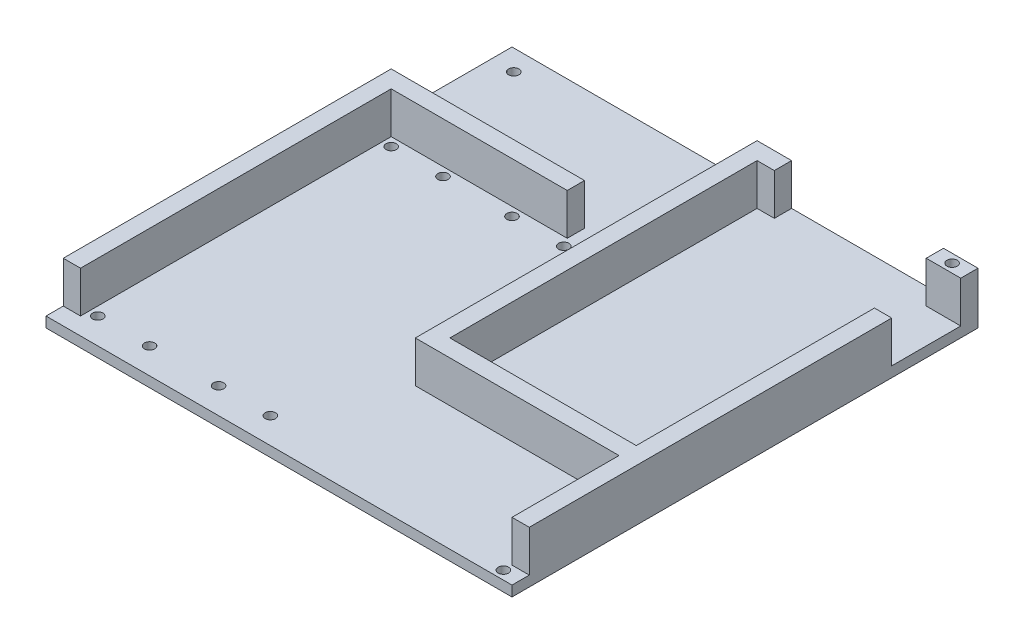
SolidWorks part; units mm, degrees
ref_plane "Front Plane" through (0, 0, 0) normal (0, 0, 1) x (1, 0, 0)
ref_plane "Top Plane" through (0, 0, 0) normal (0, 1, 0) x (1, 0, 0)
ref_plane "Right Plane" through (0, 0, 0) normal (1, 0, 0) x (0, 0, -1)
sketch "Sketch1" plane through (0, 0, 0) normal (0, 1, 0) x (1, 0, 0)
  line L1 (-65, -65) -> (65, -65)
  line L2 (-65, -65) -> (-65, 65)
  line L3 (-65, 65) -> (65, 65)
  line L4 (65, -65) -> (65, 65)
  line L5 (-65, -65) -> (65, 65) construction
  line L6 (-65, 65) -> (65, -65) construction
  line L7 (-65, -65) -> (-70, -65)
  line L8 (-65, -65) -> (-65, 65)
  line L9 (-65, 65) -> (-70, 65)
  line L10 (-70, -65) -> (-70, 65)
  point P0 (0, 0)
  dimension "D1" = 130
  dimension "D2" = 130
  dimension "D3" = 5
extrude "Boss-Extrude1" add sketch "Sketch1" along normal blind 3 contours L1 L4 L3 L2 | L10 L7 L2 L9
sketch "Sketch7" plane through (0, 3, 0) normal (0, 1, 0) x (1, 0, 0)
  line L0 (-70, -65) -> (65, -65) construction
  line L1 (-65, -65) -> (-45, -65)
  line L2 (-65, -65) -> (-65, 25)
  line L3 (-65, 25) -> (-45, 25)
  line L4 (-45, -65) -> (-45, 25)
  line L5 (-65, 22.5) -> (-45, 22.5) construction
  line L6 (-55, 25) -> (-55, -65) construction
  line L7 (-70, -65) -> (-70, 65) construction
  line L8 (-65, -20) -> (-45, -20) construction
  line L9 (-37.5, -65) -> (-37.5, 65) construction
  line L10 (-70, 65) -> (65, 65) construction
  line L11 (-10, 25) -> (-30, 25)
  line L12 (-30, -65) -> (-30, 25)
  line L13 (-10, -65) -> (-30, -65)
  line L14 (-10, -65) -> (-10, 25)
  circle A0 centre (-62.5, 22.5) radius 1.5
  circle A1 centre (-47.5, 22.5) radius 1.5
  circle A2 centre (-47.5, -62.5) radius 1.5
  circle A3 centre (-62.5, -62.5) radius 1.5
  circle A4 centre (-27.5, 22.5) radius 1.5
  circle A5 centre (-12.5, 22.5) radius 1.5
  circle A6 centre (-12.5, -62.5) radius 1.5
  circle A7 centre (-27.5, -62.5) radius 1.5
  dimension "D4" = 3
  dimension "D1" = 90
  dimension "D2" = 20
  dimension "D3" = 5
  dimension "D5" = 2.5
  dimension "D6" = 2.5
  dimension "D7" = 15
extrude "Cut-Extrude3" cut sketch "Sketch7" against normal blind 3 contours A2 | A3 | A0 | A1 | A4 | A5 | A7 | A6
sketch "Sketch8" plane through (0, 3, 0) normal (0, 1, 0) x (1, 0, 0)
  line L0 (-70, -65) -> (65, -65) construction
  line L1 (65, -65) -> (65, 65) construction
  line L2 (-70, -65) -> (65, -65)
  line L3 (65, -65) -> (65, 65)
  line L4 (-70, 65) -> (65, 65) construction
  line L5 (65, 65) -> (60, 65)
  line L6 (65, 65) -> (65, -65)
  line L7 (65, -65) -> (60, -65)
  line L8 (60, 65) -> (60, -65)
  line L9 (6, 65) -> (1, 65)
  line L10 (6, 65) -> (6, -29)
  line L11 (6, -29) -> (1, -29)
  line L12 (1, 65) -> (1, -29)
  line L14 (6, 60) -> (11, 60)
  line L15 (6, 60) -> (6, 65)
  line L16 (6, 65) -> (11, 65)
  line L17 (11, 60) -> (11, 65)
  line L18 (60, 60) -> (55, 60)
  line L19 (60, 60) -> (60, 65)
  line L20 (60, 65) -> (55, 65)
  line L21 (55, 60) -> (55, 65)
  line L22 (1, -29) -> (60, -29)
  line L23 (1, -29) -> (1, -65)
  line L24 (1, -65) -> (60, -65)
  line L25 (60, -29) -> (60, -65)
  line L26 (6, -34) -> (55, -34)
  line L27 (6, -34) -> (6, -60)
  line L28 (6, -60) -> (55, -60)
  line L29 (55, -34) -> (55, -60)
  line L30 (60, 60) -> (65, 60)
  line L31 (60, 60) -> (60, 40)
  line L32 (60, 40) -> (65, 40)
  line L33 (65, 60) -> (65, 40)
  line L34 (55, -60) -> (60, -60)
  line L35 (55, -60) -> (55, -34)
  line L36 (55, -34) -> (60, -34)
  line L37 (60, -60) -> (60, -34)
  line L38 (6, -34) -> (1, -34)
  line L39 (6, -34) -> (6, -60)
  line L40 (6, -60) -> (1, -60)
  line L41 (1, -34) -> (1, -60)
  line M22 (65, -65) -> (65, 65)
  line M23 (65, 65) -> (-70, 65)
  dimension "D1" = 5
  dimension "D2" = 5
  dimension "D3" = 54
  dimension "D4" = 5
  dimension "D5" = 5
  dimension "D6" = 5
  dimension "D7" = 5
  dimension "D8" = 94
  dimension "D9" = 5
  dimension "D10" = 20
  dimension "D11" = 5
extrude "Boss-Extrude5" add sketch "Sketch8" along normal blind 12 contours L14 L17 L10 M23 | L12 L11 L10 M23 | L21 L18 L8 M23 | L8 L30 L6 M23 | L32 L8 L2 M22 | L11 L23 L2 L8 L22 L26 L29 L28 L27
sketch "Sketch9" plane through (0, 3, 0) normal (0, 1, 0) x (1, 0, 0)
  line L0 (-70, 65) -> (1, 65) construction
  line L1 (-70, -65) -> (-70, 65) construction
  line L2 (-70, 65) -> (1, 65)
  line L3 (-70, -65) -> (-70, 65)
  line L4 (-63.5, 65) -> (-63.5, 36.7574) construction
  line L5 (-34.5, 65) -> (-34.5, 36) construction
  circle A0 centre (-63.5, 59) radius 1.5
  circle A1 centre (-63.5, 36) radius 1.5
  circle A2 centre (-5.5, 36) radius 1.5
  circle A3 centre (-5.5, 59) radius 1.5
  dimension "D2" = 6
  dimension "D1" = 23
  dimension "D3" = 35.5
  dimension "D4" = 58
extrude "Cut-Extrude4" cut sketch "Sketch9" against normal blind 9 contours A0 | A1 | A2 | A3
sketch "Sketch10" plane through (0, 3, 0) normal (0, 1, 0) x (1, 0, 0)
  line L0 (-70, -65) -> (60, -65) construction
  line L1 (-70, -65) -> (-70, 65) construction
  line L2 (-70, -65) -> (60, -65)
  line L3 (-70, -65) -> (-70, 65)
  line L4 (1, 65) -> (1, -34) construction
  line L5 (-70, 25) -> (1, 25)
  line L6 (-70, 25) -> (-70, 30)
  line L7 (-70, 30) -> (1, 30)
  line L8 (1, 25) -> (1, 30)
  line L10 (-70, -65) -> (-65, -65)
  line L11 (-70, -65) -> (-70, 25)
  line L12 (-70, 25) -> (-65, 25)
  line L13 (-65, -65) -> (-65, 25)
  line L14 (1, 25) -> (-14, 25)
  line L15 (1, 25) -> (1, 30)
  line L16 (1, 30) -> (-14, 30)
  line L17 (-14, 25) -> (-14, 30)
  line M15 (-70, -65) -> (60, -65)
  dimension "D3" = 5
  dimension "D1" = 90
  dimension "D2" = 5
  dimension "D4" = 15
extrude "Boss-Extrude6" add sketch "Sketch10" along normal blind 12 contours L5 L17 L7 L3 | L13 L5 L3 M15
ref_plane "Plane5" through (-65, 15, 65) normal (1, 0, 0) x (0, 0, -1)
sketch "Sketch12" plane through (0, 0, 0) normal (0, 1, 0) x (1, 0, 0)
  line L0 (60, -65) -> (65, -65) construction
  line L1 (-65, -65) -> (60, -65) construction
  line L2 (-70, -65) -> (-65, -65) construction
  line L3 (60, -65) -> (65, -65)
  line L4 (-65, -65) -> (60, -65)
  line L5 (-70, -65) -> (-65, -65)
  line L6 (65, -67.5) -> (48.8227, -67.5) construction
  line L7 (-70, -65) -> (65, -65)
  line L8 (-70, -65) -> (-70, -70)
  line L9 (-70, -70) -> (65, -70)
  line L10 (65, -65) -> (65, -70)
  circle A0 centre (60, -67.5) radius 1.5
  dimension "D2" = 5
  dimension "D1" = 5
extrude "Boss-Extrude7" add sketch "Sketch12" along normal blind 3 contours L10 L3 L4 L5 L8 L9
sketch "Sketch13" plane through (0, 15, 0) normal (0, 1, 0) x (1, 0, 0)
  line L0 (60, 65) -> (60, 60) construction
  line L4 (55, 65) -> (55, 60)
  line L5 (55, 60) -> (65, 60)
  line L6 (65, 60) -> (65, 65)
  line L7 (65, 65) -> (55, 65)
  line L8 (55, 65) -> (55, 60)
  line L9 (55, 60) -> (65, 60)
  line L10 (65, 60) -> (65, 65)
  line L11 (65, 65) -> (55, 65)
  circle A0 centre (60, 62.5) radius 1.5
  dimension "D1" = 0
extrude "Cut-Extrude5" cut sketch "Sketch13" against normal blind 10 contours A0 L0 | L0 A0
